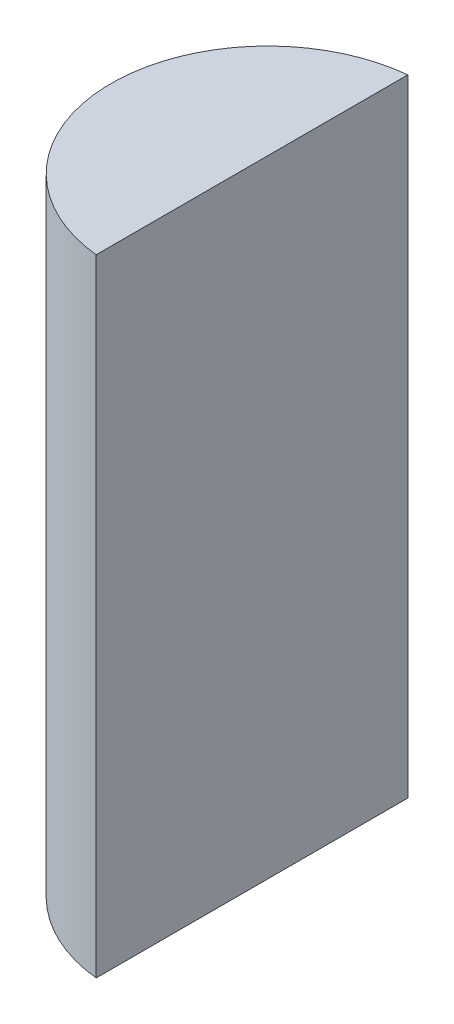
SolidWorks part; units mm, degrees
ref_plane "Front Plane" through (0, 0, 0) normal (0, 0, 1) x (1, 0, 0)
ref_plane "Top Plane" through (0, 0, 0) normal (0, 1, 0) x (1, 0, 0)
ref_plane "Right Plane" through (0, 0, 0) normal (1, 0, 0) x (0, 0, -1)
sketch "Sketch1" plane through (0, 0, 0) normal (0, 1, 0) x (1, 0, 0)
  line L1 (-5, 49.7494) -> (-5, -49.7494)
  arc A0 (-5, 49.7494) -> (-5, -49.7494) centre (0, 0) ccw
extrude "Boss-Extrude1" add sketch "Sketch1" along normal blind 200
